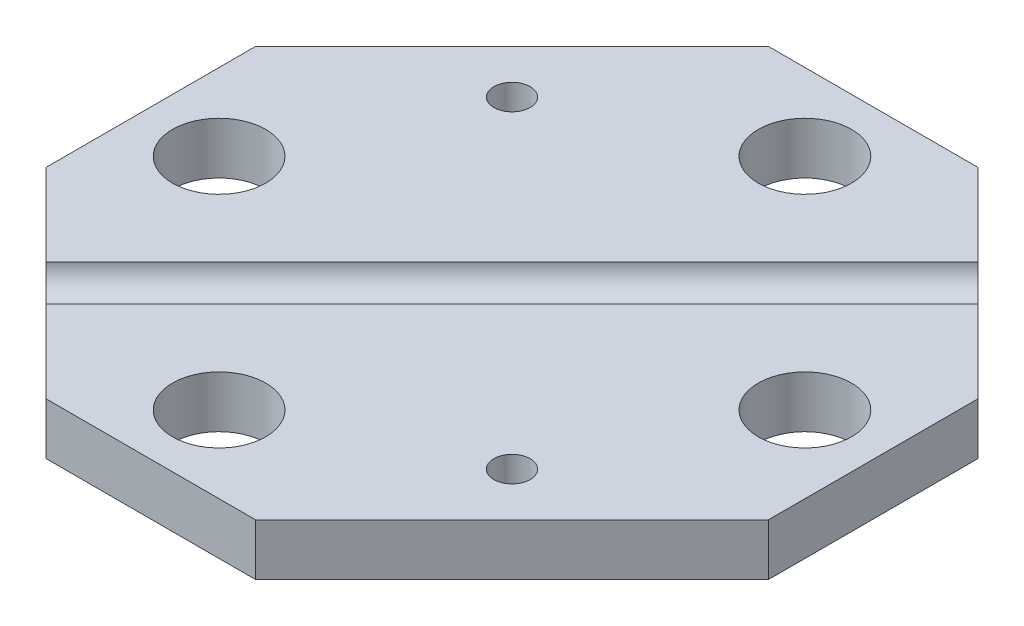
SolidWorks part; units mm, degrees
ref_plane "Front Plane" through (0, 0, 0) normal (0, 0, 1) x (1, 0, 0)
ref_plane "Top Plane" through (0, 0, 0) normal (0, 1, 0) x (1, 0, 0)
ref_plane "Right Plane" through (0, 0, 0) normal (1, 0, 0) x (0, 0, -1)
sketch "Sketch1" plane through (0, 0, 0) normal (0, 1, 0) x (1, 0, 0)
  line L0 (-40.3039, 15.5552) -> (-15.5552, 40.3039)
  line L1 (-40.3039, -40.3039) -> (40.3039, -40.3039) construction
  line L2 (-40.3039, -40.3039) -> (-40.3039, 40.3039) construction
  line L3 (-40.3039, 40.3039) -> (40.3039, 40.3039) construction
  line L4 (40.3039, -40.3039) -> (40.3039, 40.3039) construction
  line L5 (-40.3039, -40.3039) -> (40.3039, 40.3039) construction
  line L6 (-40.3039, 40.3039) -> (40.3039, -40.3039) construction
  line L7 (-27.9296, 27.9296) -> (2.476, -2.476) construction
  line L8 (-11.6661, -16.6182) -> (16.6182, 11.6661) construction
  line L9 (-11.6661, -16.6182) -> (-32.8793, 4.5951) construction
  line L10 (16.6182, 11.6661) -> (-4.5951, 32.8793) construction
  line L11 (-40.3039, 15.5552) -> (-40.3039, -4.6948)
  line L12 (-15.5552, 40.3039) -> (4.6948, 40.3039)
  line L13 (24.0428, 0.706) -> (24.0428, 20.956)
  line L14 (-0.706, -24.0428) -> (-20.956, -24.0428)
  line L15 (-32.8793, 4.5951) -> (-4.5951, 32.8793) construction
  line L16 (-18.7372, 18.7372) -> (11.6684, -11.6684) construction
  line L17 (-0.706, -24.0428) -> (24.0428, 0.706)
  line L18 (-40.3039, -4.6948) -> (-20.956, -24.0428)
  line L19 (4.6948, 40.3039) -> (24.0428, 20.956)
  circle A0 centre (-11.6661, -16.6182) radius 4.5
  circle A1 centre (16.6182, 11.6661) radius 4.5
  circle A2 centre (-4.5951, 32.8793) radius 4.5
  circle A3 centre (-32.8793, 4.5951) radius 4.5
  point P0 (0, 0)
  point P13 (2.476, -2.476)
  point P28 (11.6684, -11.6684)
  dimension "D6" = 9
  dimension "D1" = 135
  dimension "D2" = 35
  dimension "D3" = 43
  dimension "D4" = 40
  dimension "D5" = 30
  dimension "D7" = 20.25
  dimension "D8" = 20.25
  dimension "D9" = 43
  dimension "D10" = 35
  dimension "D11" = 20.25
  dimension "D12" = 20.25
extrude "Boss-Extrude1" add sketch "Sketch1" along normal blind 5
sketch "Sketch2" plane through (0, 5, 0) normal (0, 1, 0) x (1, 0, 0)
  line L0 (-27.9296, 27.9296) -> (11.6684, -11.6684) construction
  line L1 (-15.5552, 40.3039) -> (-40.3039, 15.5552) construction
  line L2 (-0.706, -24.0428) -> (24.0428, 0.706) construction
  line L3 (-18.7372, -2.476) -> (2.476, 18.7372) construction
  line L4 (-12.55, 33.7632) -> (17.502, 3.7112) construction
  line L5 (-12.55, 33.7632) -> (-33.7632, 12.55) construction
  line L6 (-33.7632, 12.55) -> (-3.7112, -17.502) construction
  line L7 (-3.7112, -17.502) -> (17.502, 3.7112) construction
  line L8 (15.7343, 5.4789) -> (13.9665, 3.7112) construction
  line L9 (13.9665, 3.7112) -> (15.7343, 1.9434) construction
  line L10 (-5.4789, -15.7343) -> (-3.7112, -13.9665) construction
  line L11 (-3.7112, -13.9665) -> (-1.9434, -15.7343) construction
  line L12 (-23.1566, 23.1566) -> (-21.3181, 21.3181) construction
  circle A0 centre (13.9665, 3.7112) radius 1.75
  circle A1 centre (-3.7112, -13.9665) radius 1.75
  circle A3 centre (-21.3181, 21.3181) radius 1.75
  point P9 (-8.1306, 8.1306)
  point P12 (2.476, 18.7372)
  dimension "D7" = 3.5
  dimension "D10" = 3.5
  dimension "D11" = 2.6
  dimension "D12" = 3.5
  dimension "D1" = 30
  dimension "D2" = 42.5
  dimension "D3" = 30
  dimension "D4" = 42.5
  dimension "D5" = 2.5
  dimension "D6" = 2.5
  dimension "D8" = 2.5
  dimension "D9" = 2.5
sketch "Sketch3" plane through (0, 5, 0) normal (0, 1, 0) x (1, 0, 0)
  line L0 (-30.63, -14.3688) -> (14.3688, 30.63) construction
  line L1 (-40.3039, -4.6948) -> (-20.956, -24.0428) construction
  line L2 (24.0428, 20.956) -> (4.6948, 40.3039) construction
sketch "Sketch4" plane through (22.4994, 0, -22.4994) normal (0.7071, 0, -0.7071) x (-0.7071, 0, -0.7071)
  line L0 (13.9984, 5) -> (8.9984, 5)
  line L1 (-2.1827, 5) -> (25.1795, 5) construction
  arc A0 (8.9984, 5) -> (13.9984, 5) centre (11.4984, 5) ccw
  point P5 (11.4984, 5)
  dimension "D1" = 5
extrude "Cut-Extrude1" cut sketch "Sketch4" against normal up to next
sketch "Sketch6" plane through (0, 5, 0) normal (0, 1, 0) x (1, 0, 0)
  line L0 (-9.8984, 9.8984) -> (-27.9296, 27.9296) construction
  line L1 (-32.3977, -12.601) -> (12.601, 32.3977) construction
  line L2 (-15.5552, 40.3039) -> (-40.3039, 15.5552) construction
  line L3 (-6.3628, 6.3628) -> (11.6684, -11.6684) construction
  line L4 (-28.8622, -16.1366) -> (16.1366, 28.8622) construction
  line L5 (-0.706, -24.0428) -> (24.0428, 0.706) construction
  circle A0 centre (-23.6869, 23.6869) radius 1.75
  circle A1 centre (7.4258, -7.4258) radius 1.75
  point P16 (0, 0)
  point P17 (0, 0)
  point P18 (0, 0)
  point P19 (0, 0)
  dimension "D1" = 3.5
  dimension "D2" = 6
  dimension "D3" = 6
extrude "Cut-Extrude3" cut sketch "Sketch6" against normal up to next
sketch "Sketch8" plane through (0, 0, 0) normal (0, -1, 0) x (1, 0, 0)
  line L0 (-30.63, 14.3688) -> (14.3688, -30.63) construction
  line L1 (-40.3039, 4.6948) -> (-20.956, 24.0428) construction
  line L2 (24.0428, -20.956) -> (4.6948, -40.3039) construction
  line L3 (6.5419, -22.8031) -> (2.6528, -18.914) construction
  line L4 (2.6528, -23.1566) -> (6.8954, -18.914) construction
  line L6 (2.6528, -23.1566) -> (-1.0093, -21.6158)
  line L7 (5.3546, -15.2518) -> (6.8954, -18.914)
  line L8 (11.6684, 11.6684) -> (-27.9296, -27.9296) construction
  line L9 (-0.706, 24.0428) -> (24.0428, -0.706) construction
  line L10 (-15.5552, -40.3039) -> (-40.3039, -15.5552) construction
  line L11 (-15.2518, 5.3546) -> (-18.914, 6.8954)
  line L12 (-23.1566, 2.6528) -> (-21.6158, -1.0093)
  circle A0 centre (-8.1306, -8.1306) radius 15.25
  circle A1 centre (4.7741, -21.0353) radius 0.95
  arc A2 (6.8954, -18.914) -> (2.6528, -23.1566) centre (4.7741, -21.0353) cw
  circle A3 centre (-21.0353, 4.7741) radius 0.95
  arc A4 (-18.914, 6.8954) -> (-23.1566, 2.6528) centre (-21.0353, 4.7741) ccw
  point P15 (4.7741, -21.0353)
  point P31 (0, 0)
  point P32 (0, 0)
  point P33 (-1.4644, -21.2687)
  point P34 (0, 0)
  point P35 (0, 0)
  point P36 (0, 0)
  dimension "D1" = 30.5
  dimension "D3" = 1.9
  dimension "D7" = 4.5
  dimension "D2" = 5.5
  dimension "D4" = 2.5
  dimension "D5" = 6
  dimension "D6" = 9
extrude "Cut-Extrude7" cut sketch "Sketch8" against normal blind 0.5 contours A0 | L11 A4 L12 A0 A3 | A2 L7 A0 L6 A1
